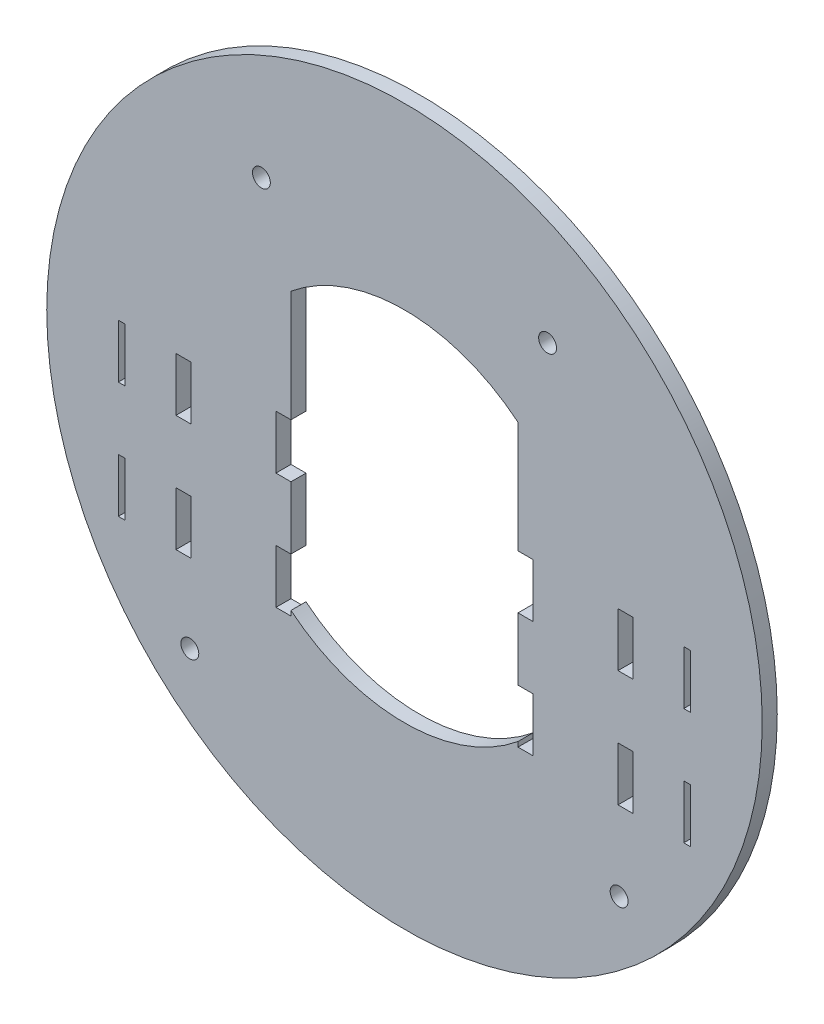
SolidWorks part; units mm, degrees
ref_plane "Front Plane" through (0, 0, 0) normal (0, 0, 1) x (1, 0, 0)
ref_plane "Top Plane" through (0, 0, 0) normal (0, 1, 0) x (1, 0, 0)
ref_plane "Right Plane" through (0, 0, 0) normal (1, 0, 0) x (0, 0, -1)
sketch "Sketch1" plane through (0, 0, 0) normal (0, 0, 1) x (1, 0, 0)
  line L2 (-40.3, 49.073) -> (-40.3, -49.073)
  line L4 (40.3, 49.073) -> (40.3, -49.073)
  circle A0 centre (0, 0) radius 127
  circle A1 centre (0, 0) radius 63.5
  dimension "D1" = 254
  dimension "D2" = 127
  dimension "D3" = 40.3
extrude "Boss-Extrude1" add sketch "Sketch1" along normal blind 5.334 contours A0 A1 | L2 A1 | L4 A1
sketch "Sketch14" plane through (0, 0, 5.334) normal (0, 0, 1) x (1, 0, 0)
  line L0 (0, 0) -> (50000, 0) construction
  line L1 (0, 0) -> (0, 50000) construction
  circle A0 centre (-76.2, -78.74) radius 3.175
  circle A1 centre (-50.8, 78.74) radius 3.175
  circle A2 centre (76.2, -78.74) radius 3.175
  circle A3 centre (50.8, 78.74) radius 3.175
  dimension "D1" = 6.35
  dimension "D2" = 6.35
  dimension "D3" = 50.8
  dimension "D4" = 78.74
  dimension "D5" = 78.74
  dimension "D6" = 76.2
extrude "BoltHoles" cut sketch "Sketch14" against normal through all
sketch "Sketch15" plane through (0, 0, 5.334) normal (0, 0, 1) x (1, 0, 0)
  line L0 (-101.6, -31.75) -> (-99.1362, -31.75)
  line L1 (-101.6, -31.75) -> (-101.6, -50.8)
  line L2 (-101.6, 9.525) -> (-99.1362, 9.525)
  line L3 (-101.6, 9.525) -> (-101.6, -9.525)
  line L4 (-101.6, -9.525) -> (-99.1362, -9.525)
  line L5 (0, 0) -> (0, 50000) construction
  line L6 (-101.6, -50.8) -> (-99.1362, -50.8)
  line L7 (-99.1362, -31.75) -> (-99.1362, -50.8)
  line L8 (-81.1362, -31.75) -> (-75.8022, -31.75)
  line L9 (-81.1362, -31.75) -> (-81.1362, -50.8)
  line L10 (-81.1362, -50.8) -> (-75.8022, -50.8)
  line L11 (-75.8022, -31.75) -> (-75.8022, -50.8)
  line L12 (-45.634, -31.75) -> (-40.3, -31.75)
  line L13 (-45.634, -31.75) -> (-45.634, -50.8)
  line L14 (-45.634, -50.8) -> (-40.3, -50.8)
  line L15 (-99.1362, 9.525) -> (-99.1362, -9.525)
  line L16 (-101.6, 9.525) -> (-99.1362, -9.525) construction
  line L17 (-101.6, -9.525) -> (-99.1362, 9.525) construction
  line L18 (-81.1362, 9.525) -> (-75.8022, 9.525)
  line L19 (-81.1362, 9.525) -> (-81.1362, -9.525)
  line L20 (-81.1362, -9.525) -> (-75.8022, -9.525)
  line L21 (-75.8022, 9.525) -> (-75.8022, -9.525)
  line L22 (-81.1362, 9.525) -> (-75.8022, -9.525) construction
  line L23 (-40.3, -31.75) -> (-40.3, -50.8)
  line L24 (-101.6, -31.75) -> (-99.1362, -50.8) construction
  line L25 (-101.6, -50.8) -> (-99.1362, -31.75) construction
  line L26 (-81.1362, -31.75) -> (-75.8022, -50.8) construction
  line L27 (-81.1362, -50.8) -> (-75.8022, -31.75) construction
  line L28 (-45.634, -31.75) -> (-40.3, -50.8) construction
  line L29 (-45.634, -50.8) -> (-40.3, -31.75) construction
  line L30 (45.634, -9.525) -> (40.3, 9.525) construction
  line L31 (45.634, 9.525) -> (40.3, -9.525) construction
  line L32 (81.1362, -9.525) -> (75.8022, 9.525) construction
  line L33 (45.634, -50.8) -> (40.3, -31.75) construction
  line L34 (45.634, -31.75) -> (40.3, -50.8) construction
  line L35 (81.1362, -50.8) -> (75.8022, -31.75) construction
  line L36 (81.1362, -31.75) -> (75.8022, -50.8) construction
  line L37 (101.6, -50.8) -> (99.1362, -31.75) construction
  line L38 (101.6, -31.75) -> (99.1362, -50.8) construction
  line L39 (81.1362, 9.525) -> (75.8022, -9.525) construction
  line L40 (101.6, -9.525) -> (99.1362, 9.525) construction
  line L41 (101.6, 9.525) -> (99.1362, -9.525) construction
  line L42 (40.3, 9.525) -> (40.3, -9.525)
  line L43 (45.634, -9.525) -> (40.3, -9.525)
  line L44 (45.634, 9.525) -> (45.634, -9.525)
  line L45 (45.634, 9.525) -> (40.3, 9.525)
  line L46 (40.3, -31.75) -> (40.3, -50.8)
  line L47 (75.8022, 9.525) -> (75.8022, -9.525)
  line L48 (81.1362, -9.525) -> (75.8022, -9.525)
  line L49 (81.1362, 9.525) -> (81.1362, -9.525)
  line L50 (81.1362, 9.525) -> (75.8022, 9.525)
  line L51 (99.1362, 9.525) -> (99.1362, -9.525)
  line L52 (45.634, -50.8) -> (40.3, -50.8)
  line L53 (-81.1362, -9.525) -> (-75.8022, 9.525) construction
  line L54 (-45.634, 9.525) -> (-40.3, 9.525)
  line L55 (-45.634, 9.525) -> (-45.634, -9.525)
  line L56 (-45.634, -9.525) -> (-40.3, -9.525)
  line L57 (-40.3, 9.525) -> (-40.3, -9.525)
  line L58 (-45.634, 9.525) -> (-40.3, -9.525) construction
  line L59 (-45.634, -9.525) -> (-40.3, 9.525) construction
  line L60 (45.634, -31.75) -> (45.634, -50.8)
  line L61 (45.634, -31.75) -> (40.3, -31.75)
  line L62 (75.8022, -31.75) -> (75.8022, -50.8)
  line L63 (81.1362, -50.8) -> (75.8022, -50.8)
  line L64 (81.1362, -31.75) -> (81.1362, -50.8)
  line L65 (81.1362, -31.75) -> (75.8022, -31.75)
  line L66 (99.1362, -31.75) -> (99.1362, -50.8)
  line L67 (101.6, -50.8) -> (99.1362, -50.8)
  line L68 (101.6, -9.525) -> (99.1362, -9.525)
  line L69 (101.6, 9.525) -> (101.6, -9.525)
  line L70 (101.6, 9.525) -> (99.1362, 9.525)
  line L71 (101.6, -31.75) -> (101.6, -50.8)
  line L72 (101.6, -31.75) -> (99.1362, -31.75)
  point P0 (-100.3681, 0)
  point P4 (-100.3681, -41.275)
  point P14 (-78.4692, -41.275)
  point P18 (-78.4692, 0)
  point P23 (-42.967, 0)
  point P26 (-42.967, -41.275)
  point P54 (42.967, -41.275)
  point P55 (42.967, 0)
  point P56 (78.4692, 0)
  point P60 (78.4692, -41.275)
  point P61 (100.3681, -41.275)
  point P62 (100.3681, 0)
  dimension "D2" = 99.1362
  dimension "D3" = 75.8022
  dimension "D5" = 19.05
  dimension "D6" = 5.334
  dimension "D7" = 40.3
  dimension "D8" = 2.4638
  dimension "D10" = 5.334
  dimension "D11" = 2
  dimension "D4" = 19.05
  dimension "D9" = 19.05
  dimension "D12" = 22.225
extrude "MotorMounts" cut sketch "Sketch15" against normal through all
